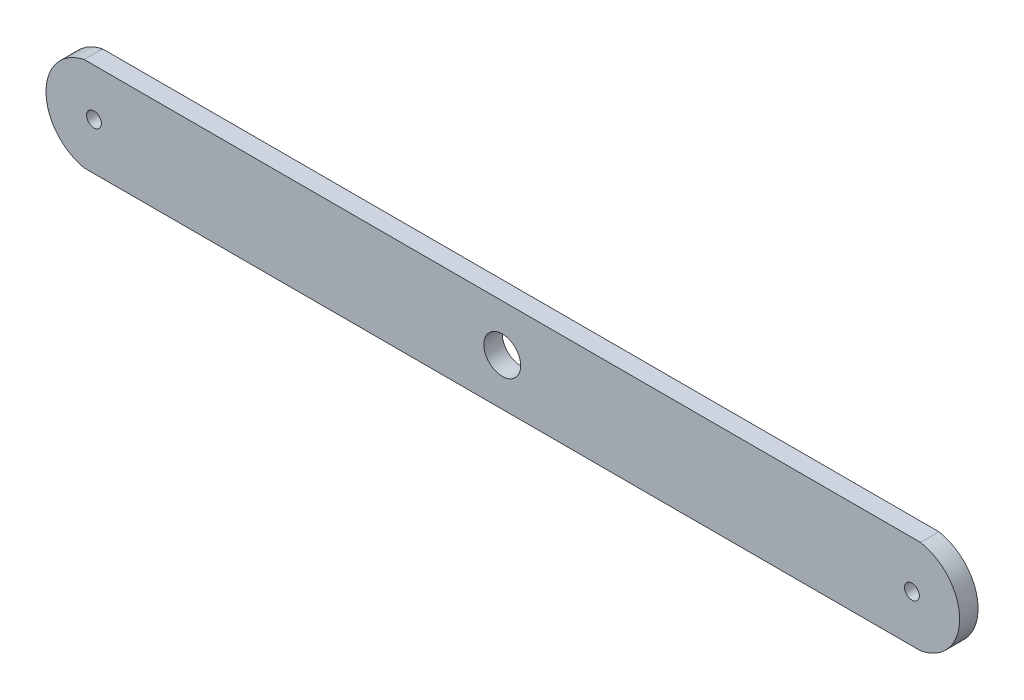
SolidWorks part; units mm, degrees
material "ABS"
ref_plane "Front Plane" through (0, 0, 0) normal (0, 0, 1) x (1, 0, 0)
ref_plane "Top Plane" through (0, 0, 0) normal (0, 1, 0) x (1, 0, 0)
ref_plane "Right Plane" through (0, 0, 0) normal (1, 0, 0) x (0, 0, -1)
sketch "Sketch1" plane through (0, 0, 0) normal (0, 0, 1) x (1, 0, 0)
  line L9 (-233.9129, 26.0043) -> (220.1383, 26.0043)
  line L11 (-233.9129, -24.9572) -> (220.1383, -24.9572)
  circle A4 centre (-228.5023, 0.5235) radius 4
  circle A5 centre (-6.8873, 0.5235) radius 10
  circle A6 centre (215.4977, 0.5235) radius 4
  arc A8 (-233.9129, 26.0043) -> (-233.9129, -24.9572) centre (-228.5023, 0.5235) ccw
  arc A9 (220.1383, -24.9572) -> (220.1383, 26.0043) centre (215.4977, 0.5235) ccw
  point P8 (0, 0)
  point P10 (0, 0)
  point P12 (0, 0)
  point P13 (-6.8873, -24.9572)
  point P14 (0, 0)
  dimension "D1" = 444
  dimension "D6" = 8
  dimension "D7" = 20
  dimension "D8" = 8
extrude "Boss-Extrude1" add sketch "Sketch1" along normal blind 10
